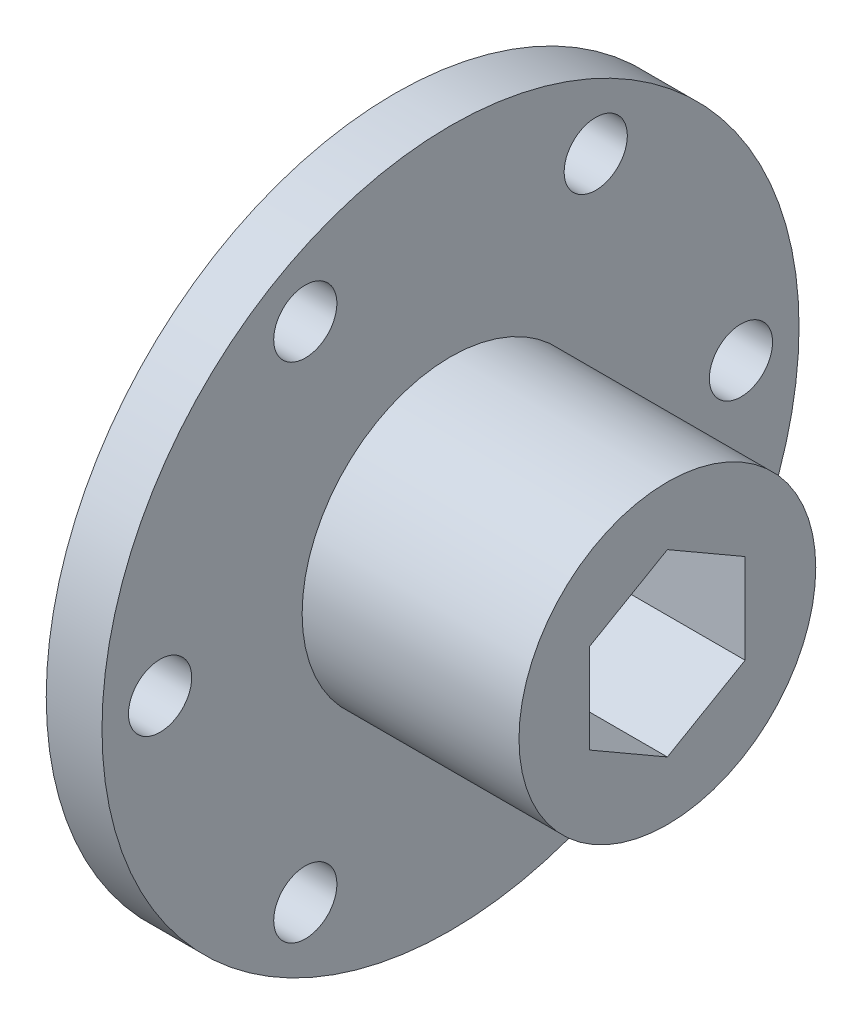
SolidWorks part; units mm, degrees
ref_plane "Front Plane" through (0, 0, 0) normal (0, 0, 1) x (1, 0, 0)
ref_plane "Top Plane" through (0, 0, 0) normal (0, 1, 0) x (1, 0, 0)
ref_plane "Right Plane" through (0, 0, 0) normal (1, 0, 0) x (0, 0, -1)
sketch "Sketch1" plane through (0, 0, 0) normal (0, 0, 1) x (1, 0, 0)
  line L0 (-17.6071, 28.575) -> (-17.6071, 0)
  line L1 (-17.6071, 0) -> (-13.0351, 0)
  line L2 (-13.0351, 0) -> (-13.0351, 28.575)
  line L3 (-13.0351, 28.575) -> (-17.6071, 28.575)
  line L4 (-17.6071, 0) -> (-13.0351, 0) construction
revolve "Revolve1" add sketch "Sketch1" angle 360 about L4
sketch "Sketch2" plane through (-13.0351, 0, 0) normal (1, 0, 0) x (0, 0, -1)
  circle A0 centre (0, 0) radius 12.1666
extrude "Boss-Extrude1" add sketch "Sketch2" along normal blind 17.78
sketch "Sketch3" plane through (-17.6071, 0, 0) normal (-1, 0, 0) x (0, 0, 1)
  line L0 (0, -7.3617) -> (6.3754, -3.6809)
  line L1 (6.3754, -3.6809) -> (6.3754, 3.6808)
  line L2 (6.3754, 3.6808) -> (0, 7.3617)
  line L3 (0, 7.3617) -> (-6.3754, 3.6808)
  line L4 (-6.3754, 3.6808) -> (-6.3754, -3.6809)
  line L5 (-6.3754, -3.6809) -> (0, -7.3617)
extrude "Cut-Extrude1" cut sketch "Sketch3" against normal through all
hole_wizard "Hole1" positions "Sketch5" profile "Sketch4" legacy
sketch "Sketch5" plane through (-17.6071, 0, 0) normal (-1, 0, 0) x (0, 0, 1)
  point P0 (11.9062, -20.6222)
  point P1 (-11.9062, -20.6222)
  point P2 (-23.8125, 0)
  point P3 (-11.9062, 20.6222)
  point P4 (11.9062, 20.6222)
  point P5 (23.8125, 0)
sketch "Sketch4" plane through (-17.6071, -20.6222, 11.9062) normal (0, 1, 0) x (0, 0, 1)
  line L0 (0, 0) -> (0, 22.352)
  line L1 (0, 22.352) -> (2.5908, 22.352)
  line L2 (2.5908, 22.352) -> (2.5908, 0)
  line L3 (2.5908, 0) -> (0, 0)
  line L4 (0, 110) -> (0, -10) construction
  dimension "Diameter" = 5.1816
  dimension "Depth" = 22.352
